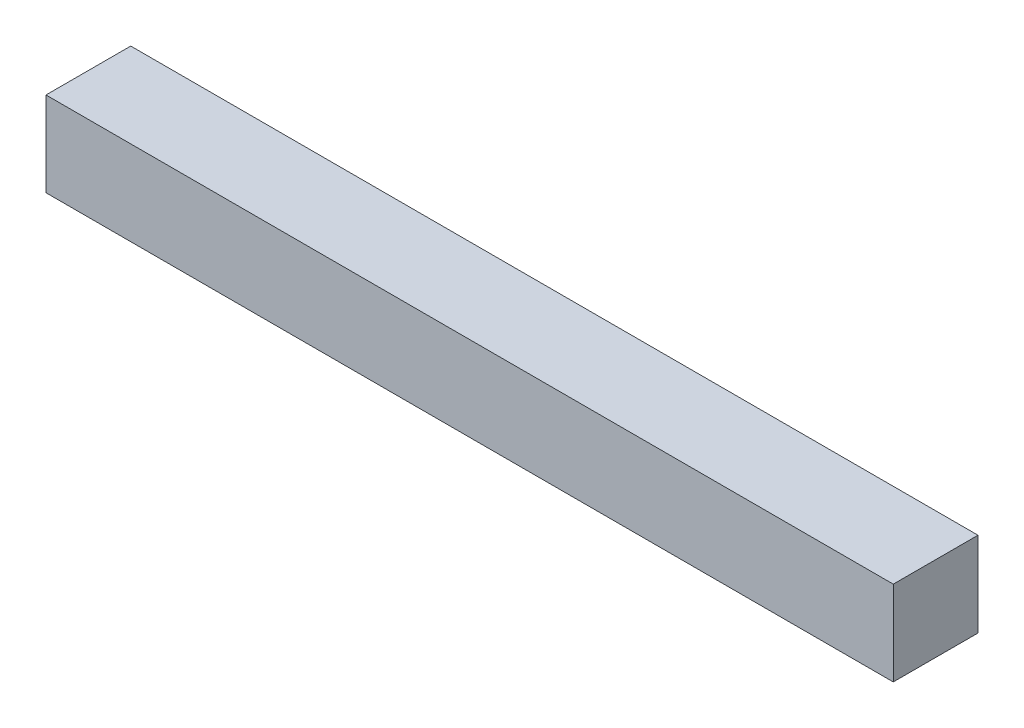
SolidWorks part; units mm, degrees
ref_plane "Front Plane" through (0, 0, 0) normal (0, 0, 1) x (1, 0, 0)
ref_plane "Top Plane" through (0, 0, 0) normal (0, 1, 0) x (1, 0, 0)
ref_plane "Right Plane" through (0, 0, 0) normal (1, 0, 0) x (0, 0, -1)
other "Configuration Table"
sketch "Sketch1" plane through (0, 0, 0) normal (0, 0, 1) x (1, 0, 0)
  line L1 (200, 500) -> (1200, 500)
  line L2 (200, 500) -> (200, 600)
  line L3 (200, 600) -> (1200, 600)
  line L4 (1200, 500) -> (1200, 600)
extrude "STORE_evaporator_2_1" add sketch "Sketch1" against normal blind 100 from offset 650 separate body
